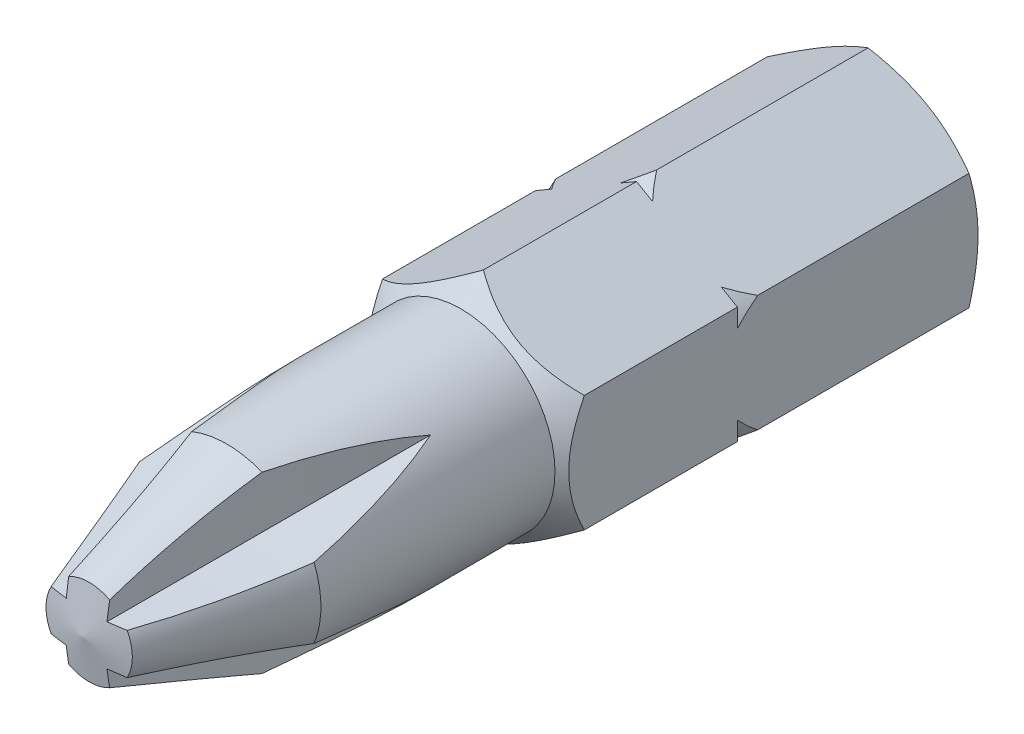
SolidWorks part; units mm, degrees
ref_plane "Front Plane" through (0, 0, 0) normal (0, 0, 1) x (1, 0, 0)
ref_plane "Top Plane" through (0, 0, 0) normal (0, 1, 0) x (1, 0, 0)
ref_plane "Right Plane" through (0, 0, 0) normal (1, 0, 0) x (0, 0, -1)
sketch "Sketch1" plane through (0, 0, 0) normal (1, 0, 0) x (0, 0, -1)
  line L0 (-12.7, 0) -> (12.7, 0) construction
  line L1 (12.7, -3.175) -> (12.7, 3.175) construction
  line L2 (-12.7, -2.9591) -> (-12.7, 2.9591) construction
  point P0 (-0.762, 0)
  point P4 (0, 0)
  point P8 (12.7, 0)
  point P11 (-12.7, 0)
  dimension "Body Diameter" = 5.9182
  dimension "Overall Length" = 25.4
  dimension "Hex Shank Size" = 6.35
  dimension "Shank Length" = 13.462
sketch "Sketch2" plane through (0, 0, 0) normal (0, 0, 1) x (1, 0, 0)
  line L0 (-1.27, 0) -> (1.27, 0) construction
  point P3 (0, 0)
  dimension "Screw Size (Thickness)" = 2.54
sketch "Sketch3" plane through (0, 0, 0) normal (1, 0, 0) x (0, 0, -1)
  line L0 (-12.7, 0) -> (12.7, 0) construction
  line L1 (-12.7, 0) -> (12.7, 0)
  line L2 (-12.7, 0) -> (-12.7, 2.9591)
  line L3 (-12.7, 2.9591) -> (-0.762, 2.9591)
  line L4 (-0.762, 2.9591) -> (-0.762, 3.81)
  line L5 (-0.762, 3.81) -> (12.7, 3.81)
  line L6 (12.7, 3.81) -> (12.7, 0)
  dimension "D1" = 3.81
revolve "Revolve1" add sketch "Sketch3" angle 360 about L1
sketch "Sketch4" plane through (0, 0, -12.7) normal (0, 0, -1) x (-1, 0, 0)
  line L1 (3.175, 1.8331) -> (0, 3.6662)
  line L2 (0, 3.6662) -> (-3.175, 1.8331)
  line L3 (-3.175, 1.8331) -> (-3.175, -1.8331)
  line L4 (-3.175, -1.8331) -> (0, -3.6662)
  line L5 (0, -3.6662) -> (3.175, -1.8331)
  line L6 (3.175, -1.8331) -> (3.175, 1.8331)
  circle A0 centre (0, 0) radius 3.175 construction
extrude "Cut-Extrude1" cut sketch "Sketch4" against normal blind 13.462 flip side to cut
sketch "Sketch6" plane through (0, 0, -12.7) normal (0, 0, -1) x (-1, 0, 0)
  circle A0 centre (0, 0) radius 2.54
  dimension "D1" = 5.08
extrude "Cut-Extrude6" cut sketch "Sketch6" against normal blind 2.54 draft 60 flip side to cut
sketch "Sketch7" plane through (0, 0, 12.7) normal (0, 0, 1) x (1, 0, 0)
  line L0 (0.635, 3.1442) -> (0.635, 0.635)
  line L1 (0.635, 0.635) -> (3.1442, 0.635)
  line L2 (0, 0) -> (1.27, 0) construction
  circle A1 centre (0, 0) radius 2.9591 construction
  arc A2 (3.1442, 0.635) -> (0.635, 3.1442) centre (0, 0) ccw
  point P5 (0.635, 0)
  point P13 (0.635, 2.8902)
  dimension "D1" = 0.254
sketch "Sketch12" plane through (0, 0, 0) normal (1, 0, 0) x (0, 0, -1)
  line L0 (-0.762, 2.9591) -> (-0.762, 3.6662)
  line L1 (-0.762, 3.6662) -> (-0.0549, 3.6662)
  line L2 (-0.762, 3.6662) -> (12.0498, 3.6662) construction
  line L3 (-0.0549, 3.6662) -> (-0.762, 2.9591)
  dimension "D1" = 45
revolve "Cut-Revolve2" cut sketch "Sketch12" angle 360 about L0
ref_plane "Plane1" through (0, 0, 0) normal (0.7071, -0.7071, 0) x (0, 0, -1)
sketch "Sketch10" plane through (0, 0, 0) normal (0.7071, -0.7071, 0) x (0, 0, -1)
  line L1 (-12.7, -2.0924) -> (-12.7, 2.0924) construction
  line L2 (-0.762, 2.9591) -> (-12.7, 2.9591) construction
  arc A0 (-12.7, 0.898) -> (-3.81, 2.9591) centre (-13.8983, 26.2697) ccw
  point P2 (-12.7, 0.898)
  point P4 (-3.81, 2.9591)
  dimension "D2" = 50.8
  dimension "D1" = 8.89
sweep "Cut-Sweep3" cut profiles "Sketch7" path "Sketch10"
pattern_circular "CirPattern3" count 4 over 360 about axis through (0, 0, 12.7) along (0, 0, -1) of "Cut-Sweep3"
sketch "Sketch11" plane through (0, 0, 0) normal (0, 1, 0) x (1, 0, 0)
  line L0 (1.27, -12.7) -> (2.9591, -8.128)
  line L1 (2.8902, -12.7) -> (0.635, -12.7) construction
  line L2 (2.9591, -12.7) -> (2.9591, -0.762) construction
  line L3 (2.9591, -8.128) -> (2.9591, -12.7)
  line L4 (2.9591, -12.7) -> (1.27, -12.7)
  dimension "D1" = 4.572
revolve "Cut-Revolve1" cut sketch "Sketch11" angle 360 about L0
sketch "Sketch13" plane through (0, 0, 0) normal (1, 0, 0) x (0, 0, -1)
  line L0 (-12.7, 0.0025) -> (-12.4609, 1.3583)
  line L1 (-8.128, 2.9591) -> (-12.7, 1.27) construction
  line L2 (-12.4609, 1.3583) -> (-12.7, 1.3583)
  line L3 (-12.7, -2.9591) -> (-12.7, 2.9591) construction
  line L4 (-12.7, 1.3583) -> (-12.7, 0.0025)
  dimension "D1" = 10
  dimension "D2" = 0.0025
revolve "Cut-Revolve4" cut sketch "Sketch13" angle 360 about L0
sketch "Sketch16" plane through (0, 0, 0) normal (1, 0, 0) x (0, 0, -1)
  line L0 (4.7625, 3.6662) -> (4.7625, 3.4122)
  line L1 (4.7625, 3.4122) -> (5.3975, 3.6662)
  line L2 (5.3975, 3.6662) -> (4.7625, 3.6662)
  line L3 (-0.0549, 3.6662) -> (12.0498, 3.6662) construction
  line L4 (12.7, -2.54) -> (12.7, 2.54) construction
  dimension "D1" = 0.635
  dimension "D2" = 0.254
  dimension "D3" = 7.9375
revolve "Cut-Revolve5" cut sketch "Sketch16" angle 360 about L0
sketch "Sketch14" plane through (0, 0, 0) normal (1, 0, 0) x (0, 0, -1)
  line L0 (-12.7, 0) -> (12.7, 0) construction
  line L1 (-12.7, 0) -> (25.4, 0) construction
  line L2 (-0.762, 0) -> (-38.862, 0) construction
  point P0 (25.4, 0)
  point P1 (-38.862, 0)
  dimension "D1" = 38.1
sketch "Sketch15" plane through (0, 0, 0) normal (1, 0, 0) x (0, 0, -1)
  line L0 (-0.762, 0) -> (50.038, 0) construction
  line L1 (-12.7, 0) -> (12.7, 0) construction
  line L2 (12.7, 0) -> (-38.1, 0) construction
  point P9 (50.038, 0)
  point P10 (-38.1, 0)
  dimension "D1" = 50.8
  dimension "D2" = 50.8
equation "\"D1@Sketch3\"=\"Hex Shank Size@Sketch1\"*.6"
equation "\"D1@Cut-Extrude1\"=\"Shank Length@Sketch1\""
equation "\"D1@Sketch6\"=\"Hex Shank Size@Sketch1\"*.8"
